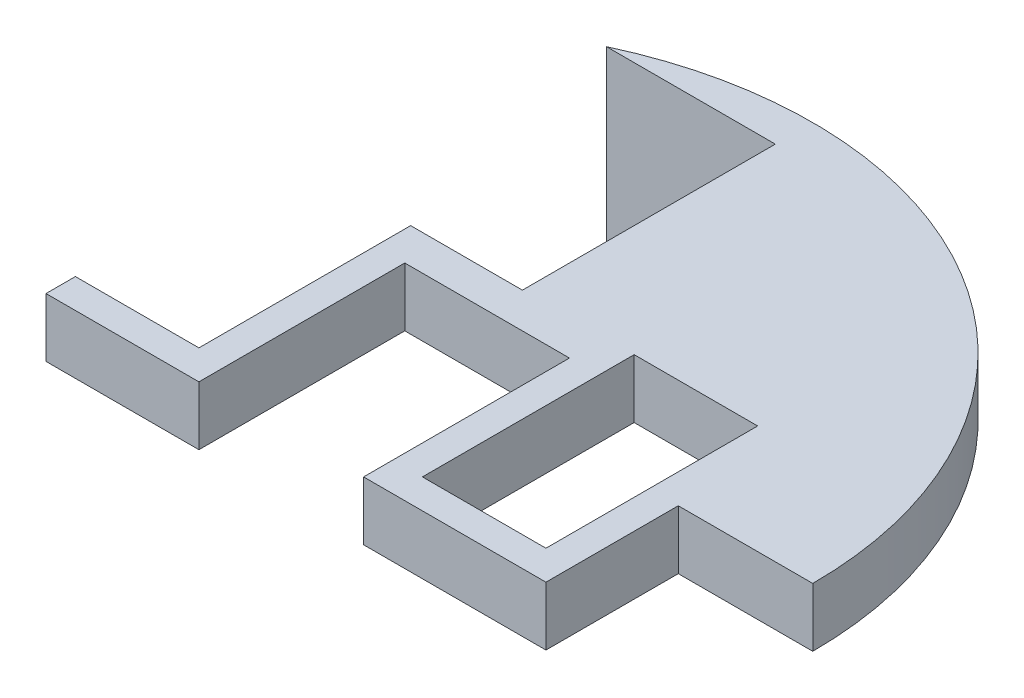
SolidWorks part; units mm, degrees
ref_plane "Front Plane" through (0, 0, 0) normal (0, 0, 1) x (1, 0, 0)
ref_plane "Top Plane" through (0, 0, 0) normal (0, 1, 0) x (1, 0, 0)
ref_plane "Right Plane" through (0, 0, 0) normal (1, 0, 0) x (0, 0, -1)
sketch "Sketch2" plane through (0, 0, 0) normal (0, 1, 0) x (1, 0, 0)
  line L1 (0, 0) -> (67.865, 0) construction
  line L6 (67.865, 0) -> (45, 0)
  line L7 (40, 18.5) -> (19, 18.5)
  line L8 (40, 18.5) -> (40, -17.5)
  line L9 (40, -17.5) -> (19, -17.5)
  line L10 (19, 18.5) -> (19, -17.5)
  line L11 (-14, 12.5) -> (14, 12.5)
  line L13 (45, 0) -> (45, -22.5)
  line L14 (45, -22.5) -> (14, -22.5)
  line L15 (14, -22.5) -> (14, 12.5)
  line L17 (19, -17.5) -> (-40, -17.5) construction
  line L18 (-40, -17.5) -> (-40, 54.8239) construction
  line L19 (-40, 18.5) -> (-19, 18.5) construction
  line L20 (-19, 18.5) -> (-19, -17.5) construction
  line L21 (-40, 18.5) -> (0, 18.5) construction
  line L22 (0, 18.5) -> (0, 61.5) construction
  line L23 (0, 61.5) -> (-40, 61.5) construction
  line L24 (-40, 61.5) -> (-40, 54.8239) construction
  line L25 (0, 61.5) -> (0, 18.5)
  line L26 (-28.6951, 61.5) -> (0, 61.5)
  line L27 (-14, 12.5) -> (-14, -22.5)
  line L28 (-14, -22.5) -> (-40, -22.5)
  line L29 (-40, -22.5) -> (-40, -17.5)
  line L30 (-40, -17.5) -> (-19, -17.5)
  line L31 (-19, 18.5) -> (-19, -17.5)
  line L32 (-19, 18.5) -> (0, 18.5)
  arc A0 (67.865, 0) -> (-28.6951, 61.5) centre (0, 0) ccw
  point P4 (30, 0)
  dimension "D1" = 67.865
  dimension "D2" = 90
  dimension "D3" = 36
  dimension "D4" = 21
  dimension "D5" = 40
  dimension "D6" = 5
  dimension "D7" = 5
  dimension "D8" = 5
  dimension "D9" = 90
  dimension "D10" = 80
  dimension "D11" = 21
  dimension "D12" = 40
  dimension "D13" = 43
  dimension "D14" = 5
  dimension "D15" = 5
  dimension "D16" = 35
  dimension "D17" = 17.5
  dimension "D18" = 9.6951
extrude "Boss-Extrude1" add sketch "Sketch2" along normal blind 10
sketch "Sketch3" plane through (0, 0, 0) normal (0, -1, 0) x (1, 0, 0)
  line L0 (0, -61.5) -> (0, -67.865)
  line L1 (0, -61.5) -> (-28.6951, -61.5)
  line L2 (-28.6951, -61.5) -> (-17.6099, -65.5404)
  line L3 (-17.6099, -65.5404) -> (-2.244, -67.8279)
  line L4 (-2.244, -67.8279) -> (0, -67.865)
  arc A1 (-28.6951, -61.5) -> (67.865, 0) centre (0, 0) ccw construction
  dimension "D1" = 11.0852
  dimension "D2" = 15.3659
extrude "Boss-Extrude2" add sketch "Sketch3" along normal blind 30
